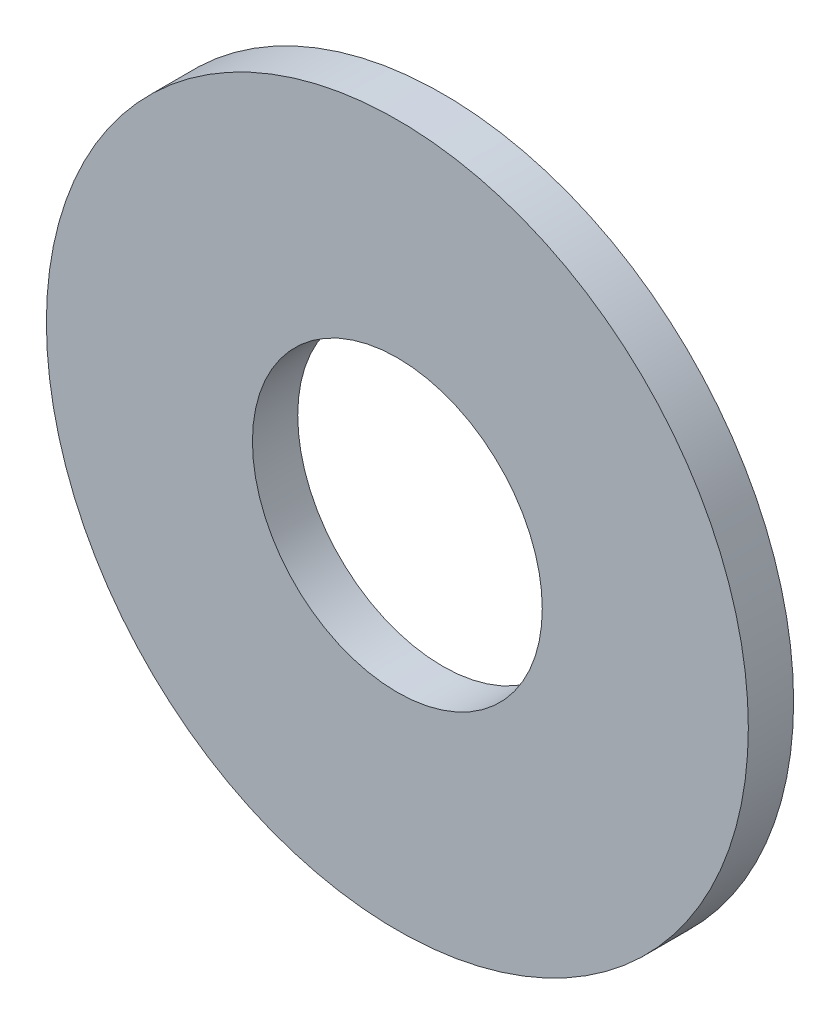
SolidWorks part; units mm, degrees
ref_plane "Front Plane" through (0, 0, 0) normal (0, 0, 1) x (1, 0, 0)
ref_plane "Top Plane" through (0, 0, 0) normal (0, 1, 0) x (1, 0, 0)
ref_plane "Right Plane" through (0, 0, 0) normal (1, 0, 0) x (0, 0, -1)
sketch "Sketch1" plane through (0, 0, 0) normal (0, 0, 1) x (1, 0, 0)
  circle A0 centre (0, 0) radius 49.2125
  dimension "D1" = 98.425
extrude "Boss-Extrude1" add sketch "Sketch1" along normal blind 6.35
sketch "Sketch2" plane through (0, 0, 6.35) normal (0, 0, 1) x (1, 0, 0)
  circle A0 centre (0, 0) radius 20.32
  dimension "D1" = 40.64
extrude "Cut-Extrude1" cut sketch "Sketch2" against normal up to surface (6.35 mm away) up to face at (49.2125, 0, 0)
